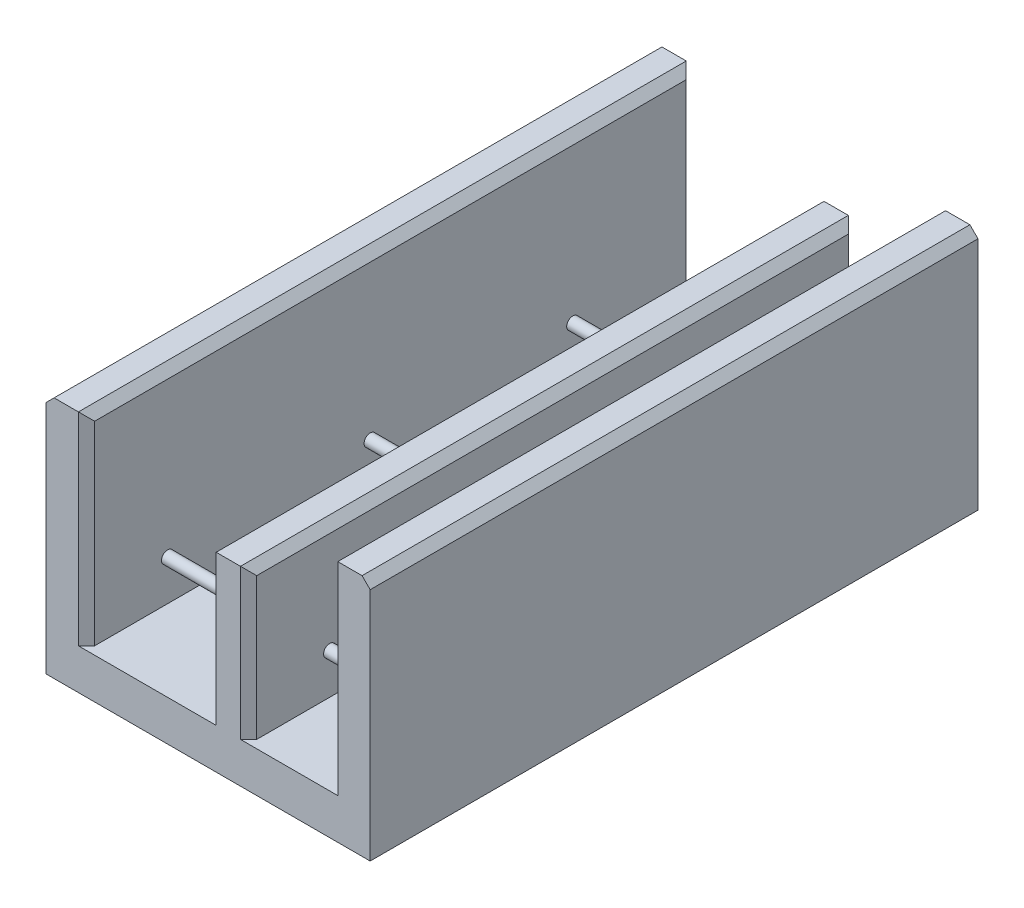
SolidWorks part; units mm, degrees
ref_plane "Alzado" through (0, 0, 0) normal (0, 0, 1) x (1, 0, 0)
ref_plane "Planta" through (0, 0, 0) normal (0, 1, 0) x (1, 0, 0)
ref_plane "Vista lateral" through (0, 0, 0) normal (1, 0, 0) x (0, 0, -1)
sketch "Croquis1" plane through (0, 0, 0) normal (0, 0, 1) x (1, 0, 0)
  line L0 (0, 0) -> (-800, 0)
  line L1 (-800, 0) -> (-800, 600)
  line L2 (-800, 600) -> (-700, 600)
  line L3 (-700, 600) -> (-700, 100)
  line L4 (-700, 100) -> (-400, 100)
  line L5 (-400, 100) -> (-400, 470)
  line L6 (-400, 470) -> (-300, 470)
  line L7 (-300, 470) -> (-300, 100)
  line L8 (-300, 100) -> (-100, 100)
  line L9 (-100, 100) -> (-100, 600)
  line L10 (-100, 600) -> (0, 600)
  line L11 (0, 600) -> (0, 0)
  dimension "D1" = 800
  dimension "D2" = 600
  dimension "D3" = 100
  dimension "D4" = 500
  dimension "D5" = 300
  dimension "D6" = 370
  dimension "D7" = 100
  dimension "D8" = 370
  dimension "D9" = 200
extrude "Saliente-Extruir1" add sketch "Croquis1" along normal blind 1500
chamfer "Chaflán2" distance 20 angle 45 14 edges at (-100, 350, 0) (0, 600, 750) (-700, 350, 0) (-700, 600, 750) (-700, 350, 1500) (-100, 350, 1500) (-300, 285, 0) (-300, 285, 1500) (-300, 470, 750) (-400, 285, 0) (-400, 285, 1500) (-400, 470, 750) (-800, 600, 750) (-100, 600, 750)
sketch "Croquis2" plane through (-800, 0, 0) normal (-1, 0, 0) x (0, 0, 1)
  line L0 (0, 580) -> (0, 0) construction
  circle A0 centre (300, 200) radius 15
  dimension "D3" = 30
  dimension "D1" = 300
extrude "Saliente-Extruir2" add sketch "Croquis2" against normal up to surface (700 mm away) up to face at (-100, 340, 750)
pattern_linear "MatrizL1" count 3 spacing 500 along (0, 0, 1) of "Saliente-Extruir2"
